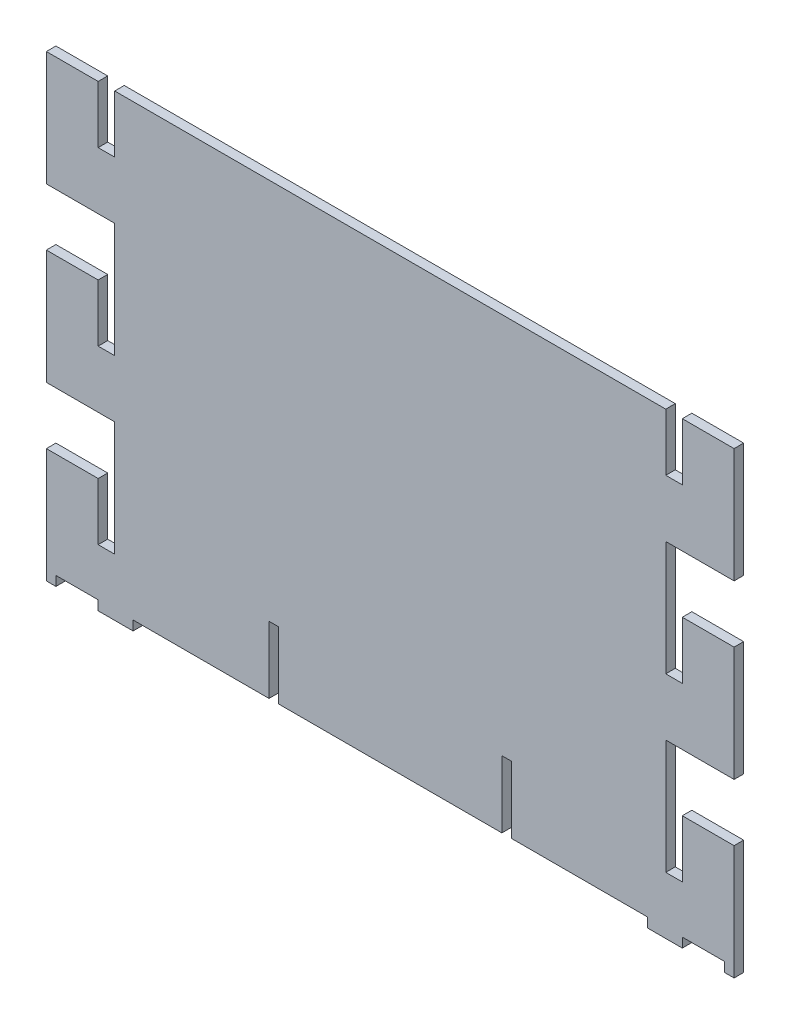
SolidWorks part; units mm, degrees
material "Plywood"
ref_plane "Front Plane" through (0, 0, 0) normal (0, 0, 1) x (1, 0, 0)
ref_plane "Top Plane" through (0, 0, 0) normal (0, 1, 0) x (1, 0, 0)
ref_plane "Right Plane" through (0, 0, 0) normal (1, 0, 0) x (0, 0, -1)
sketch "Sketch1" plane through (0, 0, 0) normal (0, 1, 0) x (1, 0, 0)
  line L0 (-381, -659.9114) -> (381, -659.9114) construction
  line L1 (-381, -659.9114) -> (381, -659.9114)
  line L2 (-381, -647.2114) -> (381, -647.2114)
  line L3 (-381, -647.2114) -> (-381, -659.9114)
  line L4 (381, -647.2114) -> (381, -659.9114)
  dimension "D1" = 12.7
extrude "Boss-Extrude1" add sketch "Sketch1" along normal blind 609.6
sketch "Sketch2" plane through (381, 0, 0) normal (1, 0, 0) x (0, 0, -1)
  line L4 (-659.9114, 0) -> (-647.2114, 0)
  line L5 (-647.2114, 0) -> (-647.2114, 609.6)
  line L6 (-647.2114, 609.6) -> (-659.9114, 609.6)
  line L7 (-659.9114, 609.6) -> (-659.9114, 0)
  line L8 (-659.9114, 0) -> (-647.2114, 0)
  line L9 (-647.2114, 0) -> (-647.2114, 609.6)
  line L10 (-647.2114, 609.6) -> (-659.9114, 609.6)
  line L11 (-659.9114, 609.6) -> (-659.9114, 0)
  dimension "D1" = 0
extrude "Boss-Extrude2" add sketch "Sketch2" along normal blind 76.2
mirror "Mirror1" about plane through (0, 0, 0) normal (1, 0, 0) of "Boss-Extrude2"
sketch "Sketch3" plane through (0, 0, 659.9114) normal (0, 0, 1) x (1, 0, 0)
  line L0 (-457.2, 457.2) -> (457.2, 457.2) construction
  line L1 (-457.2, 457.2) -> (457.2, 457.2) construction
  line L2 (-457.2, 533.4) -> (457.2, 533.4) construction
  line L3 (-457.2, 0) -> (457.2, 0) construction
  line L4 (-457.2, 533.4) -> (457.2, 533.4) construction
  line L5 (-457.2, 609.6) -> (457.2, 609.6) construction
  line L6 (-457.2, 76.2) -> (457.2, 76.2) construction
  line L7 (-457.2, 609.6) -> (457.2, 609.6) construction
  line L8 (-388.3323, 0) -> (-388.3323, 609.6) construction
  line L9 (-366.3353, 0) -> (-366.3353, 609.6) construction
  line L10 (366.3353, 0) -> (366.3353, 609.6) construction
  line L26 (388.3323, 0) -> (388.3323, 609.6) construction
  line L44 (-457.2, 152.4) -> (457.2, 152.4) construction
  line L62 (-457.2, 457.2) -> (457.2, 457.2) construction
  line L63 (-457.2, 457.2) -> (457.2, 457.2) construction
  line L64 (-457.2, 533.4) -> (457.2, 533.4) construction
  line L65 (-457.2, 0) -> (457.2, 0) construction
  line L66 (-457.2, 533.4) -> (457.2, 533.4) construction
  line L67 (-457.2, 609.6) -> (457.2, 609.6) construction
  line L68 (-457.2, 76.2) -> (457.2, 76.2) construction
  line L69 (-457.2, 609.6) -> (457.2, 609.6) construction
  line L70 (-388.3323, 0) -> (-388.3323, 609.6) construction
  line L71 (-366.3353, 0) -> (-366.3353, 609.6) construction
  line L72 (366.3353, 0) -> (366.3353, 609.6) construction
  line L73 (388.3323, 0) -> (388.3323, 609.6) construction
  line L93 (-457.2, 152.4) -> (457.2, 152.4) construction
  line L94 (-457.2, 304.8) -> (457.2, 304.8) construction
  line L95 (-457.2, 609.6) -> (-457.2, 0) construction
  line L113 (457.2, 609.6) -> (457.2, 0) construction
  line L114 (-457.2, 228.6) -> (457.2, 228.6) construction
  line L115 (-457.2, 381) -> (457.2, 381) construction
  line L116 (0, 609.6) -> (0, 0) construction
  line L117 (366.3353, 609.6) -> (-366.3353, 609.6)
  line L118 (-366.3353, 609.6) -> (-366.3353, 533.4)
  line L119 (-366.3353, 533.4) -> (-388.3323, 533.4)
  line L120 (-388.3323, 533.4) -> (-388.3323, 609.6)
  line L121 (-388.3323, 609.6) -> (-457.2, 609.6)
  line L122 (-457.2, 609.6) -> (-457.2, 457.2)
  line L123 (-457.2, 457.2) -> (-366.3353, 457.2)
  line L124 (-366.3353, 457.2) -> (-366.3353, 304.8)
  line L125 (-366.3353, 304.8) -> (-388.3323, 304.8)
  line L126 (-388.3323, 304.8) -> (-388.3323, 381)
  line L127 (-388.3323, 381) -> (-457.2, 381)
  line L128 (-457.2, 381) -> (-457.2, 228.6)
  line L129 (-457.2, 228.6) -> (-366.3353, 228.6)
  line L130 (-366.3353, 228.6) -> (-366.3353, 76.2)
  line L131 (-366.3353, 76.2) -> (-388.3323, 76.2)
  line L132 (-388.3323, 76.2) -> (-388.3323, 152.4)
  line L133 (-388.3323, 152.4) -> (-457.2, 152.4)
  line L134 (-457.2, 152.4) -> (-457.2, 0)
  line L135 (-457.2, 0) -> (457.2, 0)
  line L136 (366.3353, 0) -> (366.3353, 609.6) construction
  line L137 (388.3323, 0) -> (388.3323, 609.6) construction
  line L138 (457.2, 152.4) -> (457.2, 0)
  line L139 (388.3323, 152.4) -> (457.2, 152.4)
  line L140 (388.3323, 76.2) -> (388.3323, 152.4)
  line L141 (366.3353, 76.2) -> (388.3323, 76.2)
  line L142 (366.3353, 228.6) -> (366.3353, 76.2)
  line L143 (457.2, 228.6) -> (366.3353, 228.6)
  line L144 (457.2, 381) -> (457.2, 228.6)
  line L145 (388.3323, 381) -> (457.2, 381)
  line L146 (388.3323, 304.8) -> (388.3323, 381)
  line L147 (366.3353, 304.8) -> (388.3323, 304.8)
  line L148 (366.3353, 457.2) -> (366.3353, 304.8)
  line L149 (457.2, 457.2) -> (366.3353, 457.2)
  line L150 (457.2, 609.6) -> (457.2, 457.2)
  line L151 (388.3323, 609.6) -> (457.2, 609.6)
  line L152 (388.3323, 533.4) -> (388.3323, 609.6)
  line L153 (366.3353, 533.4) -> (388.3323, 533.4)
  line L154 (366.3353, 609.6) -> (366.3353, 533.4)
  dimension "D1" = 76.2
  dimension "D2" = 76.2
extrude "Cut-Extrude1" cut sketch "Sketch3" against normal up to vertex (12.7 mm away) flip side to cut
sketch "Sketch4" plane through (0, 0, 659.9114) normal (0, 0, 1) x (1, 0, 0)
  line L0 (0, 0) -> (0, 609.6)
  line L1 (-366.3353, 609.6) -> (366.3353, 609.6) construction
sketch "Sketch6" plane through (0, 609.6, 0) normal (0, 1, 0) x (1, 0, 0)
  line L20 (-444.5, -647.2114) -> (-444.5, -659.9114)
  line L21 (-444.5, -659.9114) -> (-388.3323, -659.9114)
  line L22 (-388.3323, -659.9114) -> (-388.3323, -647.2114)
  line L23 (-388.3323, -647.2114) -> (-444.5, -647.2114)
  line L24 (-444.5, -647.2114) -> (-444.5, -659.9114)
  line L25 (-444.5, -659.9114) -> (-388.3323, -659.9114)
  line L26 (-388.3323, -659.9114) -> (-388.3323, -647.2114)
  line L27 (-388.3323, -647.2114) -> (-444.5, -647.2114)
  line L28 (341.9177, -659.9114) -> (341.9177, -647.2114)
  line L29 (-341.9177, -659.9114) -> (341.9177, -659.9114)
  line L30 (-341.9177, -647.2114) -> (-341.9177, -659.9114)
  line L31 (341.9177, -647.2114) -> (-341.9177, -647.2114)
  line L32 (341.9177, -659.9114) -> (341.9177, -647.2114)
  line L33 (-341.9177, -659.9114) -> (341.9177, -659.9114)
  line L34 (-341.9177, -647.2114) -> (-341.9177, -659.9114)
  line L35 (341.9177, -647.2114) -> (-341.9177, -647.2114)
  line L36 (388.3323, -647.2114) -> (388.3323, -659.9114)
  line L37 (444.5, -647.2114) -> (388.3323, -647.2114)
  line L38 (444.5, -659.9114) -> (444.5, -647.2114)
  line L39 (388.3323, -659.9114) -> (444.5, -659.9114)
  line L48 (388.3323, -647.2114) -> (388.3323, -659.9114)
  line L49 (444.5, -647.2114) -> (388.3323, -647.2114)
  line L50 (444.5, -659.9114) -> (444.5, -647.2114)
  line L51 (388.3323, -659.9114) -> (444.5, -659.9114)
  dimension "D1" = 0
  dimension "D2" = 0
  dimension "D3" = 0
extrude "Cut-Extrude2" cut sketch "Sketch6" against normal up to vertex (12.7 mm away)
ref_plane "Plane1" through (0, 304.8, 0) normal (0, -1, 0) x (-1, 0, 0)
sketch "Sketch7" plane through (0, 0, 659.9114) normal (0, 0, 1) x (1, 0, 0)
  line L1171 (148.4706, 508) -> (161.1706, 508)
  line L1172 (161.1706, 508) -> (161.1706, 596.9)
  line L1173 (161.1706, 596.9) -> (148.4706, 596.9)
  line L1174 (148.4706, 596.9) -> (148.4706, 508)
  line L1175 (148.4706, 508) -> (161.1706, 508)
  line L1176 (161.1706, 508) -> (161.1706, 596.9)
  line L1177 (161.1706, 596.9) -> (148.4706, 596.9)
  line L1178 (148.4706, 596.9) -> (148.4706, 508)
  line L1179 (-148.4706, 596.9) -> (-161.1706, 596.9)
  line L1180 (-148.4706, 508) -> (-148.4706, 596.9)
  line L1181 (-161.1706, 508) -> (-148.4706, 508)
  line L1182 (-161.1706, 596.9) -> (-161.1706, 508)
  line L1183 (-148.4706, 596.9) -> (-161.1706, 596.9)
  line L1184 (-148.4706, 508) -> (-148.4706, 596.9)
  line L1185 (-161.1706, 508) -> (-148.4706, 508)
  line L1186 (-161.1706, 596.9) -> (-161.1706, 508)
  dimension "D1" = 0
  dimension "D2" = 0
extrude "Cut-Extrude3" cut sketch "Sketch7" against normal up to vertex (12.7 mm away)
mirror "Mirror2" about plane through (0, 304.8, 0) normal (0, -1, 0) of "Cut-Extrude3", "Cut-Extrude2"
sketch "Sketch8" plane through (0, 609.6, 0) normal (0, 1, 0) x (1, 0, 0)
  line L16 (366.3353, -647.2114) -> (366.3353, -659.9114) construction
  line L17 (-366.3353, -647.2114) -> (-366.3353, -659.9114) construction
  line L18 (366.3353, -647.2114) -> (366.3353, -659.9114)
  line L19 (-366.3353, -647.2114) -> (-366.3353, -659.9114)
  line L20 (-366.3353, -647.2114) -> (366.3353, -647.2114)
  line L21 (366.3353, -659.9114) -> (-366.3353, -659.9114)
extrude "Boss-Extrude3" add sketch "Sketch8" against normal up to vertex
sketch "Sketch9" plane through (0, 609.6, 0) normal (0, 1, 0) x (1, 0, 0)
  line L0 (388.3323, -647.2114) -> (388.3323, -659.9114) construction
  line L1 (457.2, -647.2114) -> (457.2, -659.9114) construction
  line L2 (-457.2, -647.2114) -> (-457.2, -659.9114) construction
  line L3 (-388.3323, -659.9114) -> (-388.3323, -647.2114) construction
  line L4 (388.3323, -647.2114) -> (388.3323, -659.9114)
  line L5 (457.2, -647.2114) -> (457.2, -659.9114)
  line L6 (-457.2, -647.2114) -> (-457.2, -659.9114)
  line L7 (-388.3323, -659.9114) -> (-388.3323, -647.2114)
  line L8 (-457.2, -659.9114) -> (-388.3323, -659.9114)
  line L9 (-388.3323, -647.2114) -> (-457.2, -647.2114)
  line L10 (388.3323, -659.9114) -> (457.2, -659.9114)
  line L11 (457.2, -647.2114) -> (388.3323, -647.2114)
extrude "Boss-Extrude4" add sketch "Sketch9" against normal up to vertex
